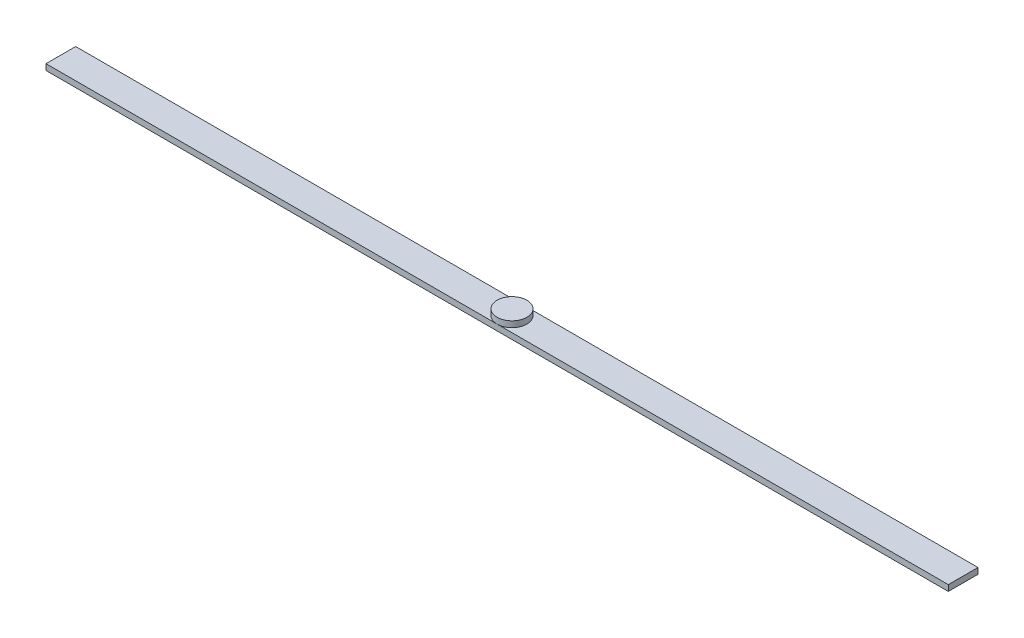
SolidWorks part; units mm, degrees
ref_plane "前视基准面" through (0, 0, 0) normal (0, 0, 1) x (1, 0, 0)
ref_plane "上视基准面" through (0, 0, 0) normal (0, 1, 0) x (1, 0, 0)
ref_plane "右视基准面" through (0, 0, 0) normal (1, 0, 0) x (0, 0, -1)
other "Configuration Table"
sketch "草图1" plane through (0, 0, 0) normal (0, 1, 0) x (1, 0, 0)
  line L1 (-152, -5) -> (152, -5)
  line L2 (-152, -5) -> (-152, 5)
  line L3 (-152, 5) -> (152, 5)
  line L4 (152, -5) -> (152, 5)
  line L5 (-152, -5) -> (152, 5) construction
  line L6 (-152, 5) -> (152, -5) construction
  point P0 (0, 0)
  dimension "D1" = 304
  dimension "D2" = 10
extrude "凸台-拉伸1" add sketch "草图1" along normal blind 2
sketch "草图2" plane through (0, 2, 0) normal (0, 1, 0) x (1, 0, 0)
  circle A0 centre (0, 0) radius 5
extrude "凸台-拉伸2" add sketch "草图2" along normal blind 2
